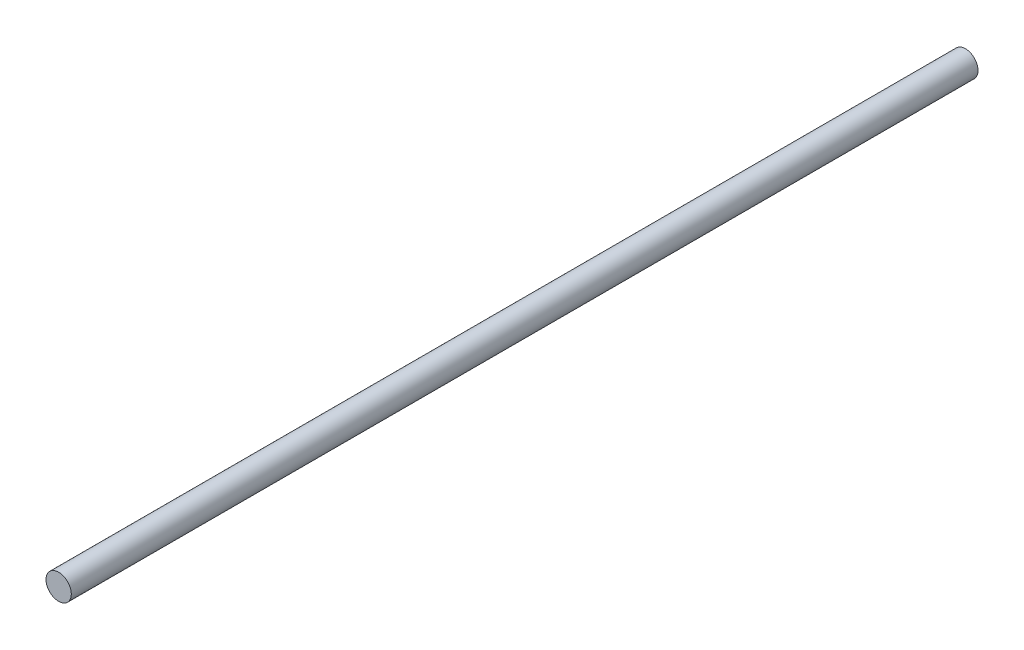
SolidWorks part; units mm, degrees
material "Alloy Steel"
ref_plane "Front Plane" through (0, 0, 0) normal (0, 0, 1) x (1, 0, 0)
ref_plane "Top Plane" through (0, 0, 0) normal (0, 1, 0) x (1, 0, 0)
ref_plane "Right Plane" through (0, 0, 0) normal (1, 0, 0) x (0, 0, -1)
sketch "Sketch1" plane through (0, 0, 0) normal (0, 0, 1) x (1, 0, 0)
  circle A0 centre (0, 0) radius 1.5
  dimension "D1" = 3
extrude "Boss-Extrude1" add sketch "Sketch1" along normal blind 107.6
